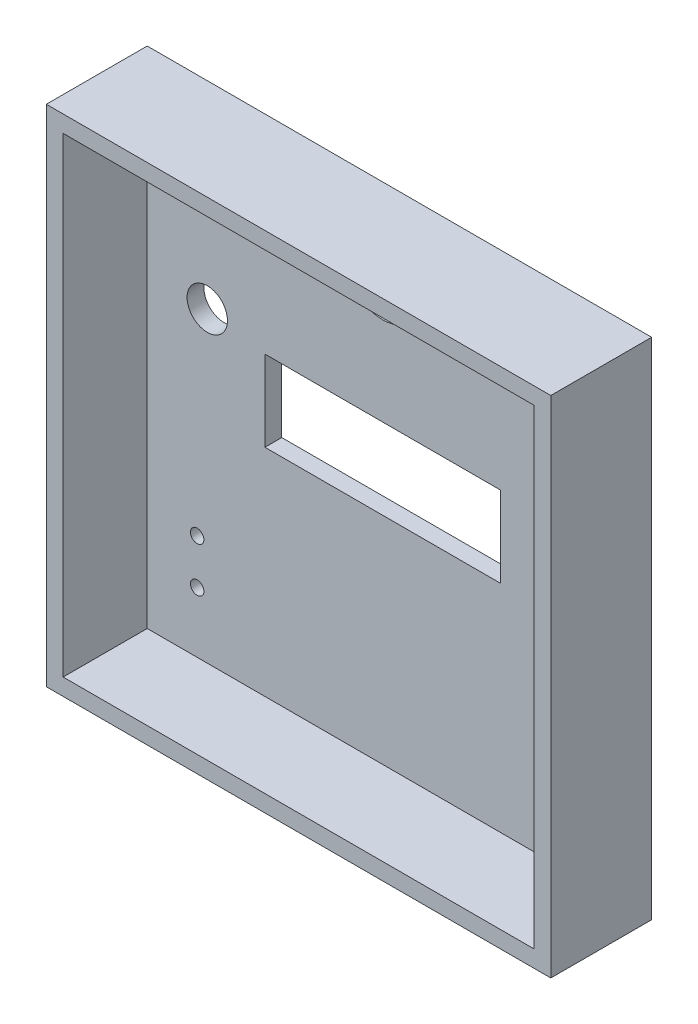
SolidWorks part; units mm, degrees
ref_plane "Front Plane" through (0, 0, 0) normal (0, 0, 1) x (1, 0, 0)
ref_plane "Top Plane" through (0, 0, 0) normal (0, 1, 0) x (1, 0, 0)
ref_plane "Right Plane" through (0, 0, 0) normal (1, 0, 0) x (0, 0, -1)
sketch "Sketch4" plane through (0, 0, 0) normal (0, 0, 1) x (1, 0, 0)
  line L1 (-75, 75) -> (75, 75)
  line L2 (-75, 75) -> (-75, -75)
  line L3 (-75, -75) -> (75, -75)
  line L4 (75, 75) -> (75, -75)
  line L5 (-75, 75) -> (75, -75) construction
  line L6 (-75, -75) -> (75, 75) construction
  point P0 (0, 0)
  dimension "D1" = 150
  dimension "D2" = 150
extrude "Boss-Extrude1" add sketch "Sketch4" along normal blind 30
shell "Shell2" thickness 5
sketch "Sketch5" plane through (0, 0, 0) normal (0, 0, -1) x (-1, 0, 0)
  circle A0 centre (0, 55.5038) radius 11
extrude "Cut-Extrude1" cut sketch "Sketch5" against normal blind 10
sketch "Sketch6" plane through (0, 0, 0) normal (0, 0, -1) x (-1, 0, 0)
  line L1 (-35, 18.1688) -> (35, 18.1688)
  line L2 (-35, 18.1688) -> (-35, -5.8312)
  line L3 (-35, -5.8312) -> (35, -5.8312)
  line L4 (35, 18.1688) -> (35, -5.8312)
  line L5 (-35, 18.1688) -> (35, -5.8312) construction
  line L6 (-35, -5.8312) -> (35, 18.1688) construction
  point P0 (0, 6.1688)
  dimension "D1" = 24
  dimension "D2" = 70
extrude "Cut-Extrude2" cut sketch "Sketch6" against normal blind 10
sketch "Sketch7" plane through (0, 0, 0) normal (0, 0, -1) x (-1, 0, 0)
  circle A0 centre (52.1424, 21.1959) radius 6
extrude "Cut-Extrude3" cut sketch "Sketch7" against normal blind 10
sketch "Sketch8" plane through (0, 0, 0) normal (0, 0, -1) x (-1, 0, 0)
  circle A0 centre (-48.9525, -41.3905) radius 2.5
extrude "Cut-Extrude4" cut sketch "Sketch8" against normal blind 10
sketch "Sketch10" plane through (0, 0, 0) normal (0, 0, -1) x (-1, 0, 0)
  circle A0 centre (55.1473, -52.0314) radius 2
  circle A1 centre (55.1473, -38.7312) radius 2
extrude "Cut-Extrude5" cut sketch "Sketch10" against normal blind 10
